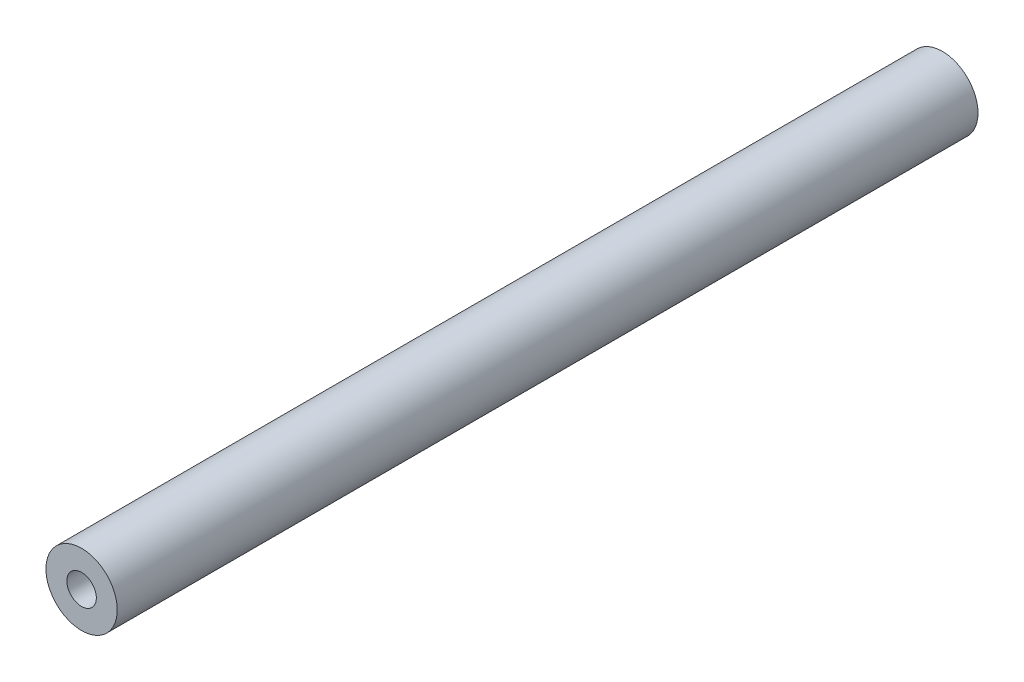
SolidWorks part; units mm, degrees
ref_plane "Front Plane" through (0, 0, 0) normal (0, 0, 1) x (1, 0, 0)
ref_plane "Top Plane" through (0, 0, 0) normal (0, 1, 0) x (1, 0, 0)
ref_plane "Right Plane" through (0, 0, 0) normal (1, 0, 0) x (0, 0, -1)
sketch "Sketch2" plane through (0, 0, 0) normal (0, 0, 1) x (1, 0, 0)
  circle A0 centre (0, 0) radius 7.366
  circle A1 centre (0, 0) radius 3.048
  dimension "D1" = 14.732
  dimension "D2" = 6.096
extrude "Boss-Extrude1" add sketch "Sketch2" along normal blind 177.8
